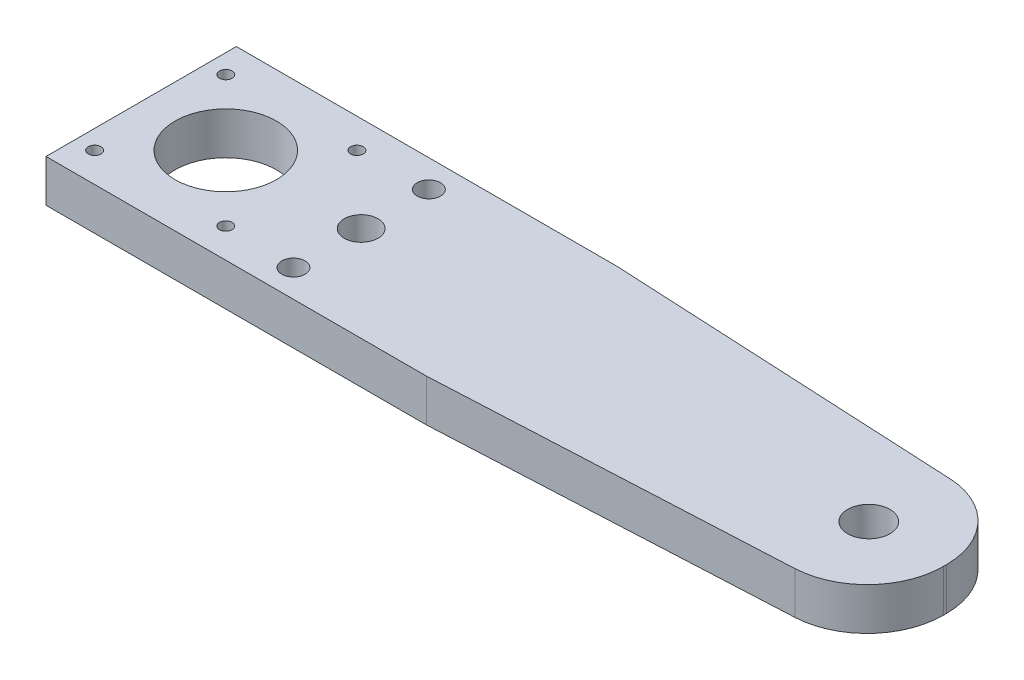
SolidWorks part; units mm, degrees
ref_plane "Front Plane" through (0, 0, 0) normal (0, 0, 1) x (1, 0, 0)
ref_plane "Top Plane" through (0, 0, 0) normal (0, 1, 0) x (1, 0, 0)
ref_plane "Right Plane" through (0, 0, 0) normal (1, 0, 0) x (0, 0, -1)
sketch "Sketch1" plane through (0, 0, 0) normal (0, 1, 0) x (1, 0, 0)
  line L1 (-95, 22.5) -> (95, 22.5)
  line L2 (-95, 22.5) -> (-95, -22.5)
  line L3 (-95, -22.5) -> (95, -22.5)
  line L4 (95, 22.5) -> (95, -22.5)
  line L5 (-95, 22.5) -> (95, -22.5) construction
  line L6 (-95, -22.5) -> (95, 22.5) construction
  point P0 (0, 0)
  dimension "D1" = 45
  dimension "D2" = 190
extrude "Boss-Extrude1" add sketch "Sketch1" along normal blind 10
sketch "Sketch2" plane through (0, 10, 0) normal (0, 1, 0) x (1, 0, 0)
  line L0 (-95, 0) -> (-75, 0) construction
  line L1 (-95, 22.5) -> (-95, -22.5) construction
  line L2 (-75, 0) -> (-43, 0) construction
  line L3 (-90.5, 15.5) -> (-59.5, 15.5) construction
  line L4 (-90.5, 15.5) -> (-90.5, -15.5) construction
  line L5 (-90.5, -15.5) -> (-59.5, -15.5) construction
  line L6 (-59.5, 15.5) -> (-59.5, -15.5) construction
  line L7 (-90.5, 15.5) -> (-59.5, -15.5) construction
  line L8 (-90.5, -15.5) -> (-59.5, 15.5) construction
  line L9 (-43, 0) -> (-43, 16) construction
  line L10 (-43, 0) -> (77, 0) construction
  circle A0 centre (-90.5, 15.5) radius 1.5
  circle A1 centre (-59.5, 15.5) radius 1.5
  circle A2 centre (-90.5, -15.5) radius 1.5
  circle A3 centre (-59.5, -15.5) radius 1.5
  circle A4 centre (-75, 0) radius 12
  circle A5 centre (-43, 0) radius 4
  circle A6 centre (-43, 16) radius 2.75
  circle A7 centre (-43, -16) radius 2.75
  circle A8 centre (77, 0) radius 5
  dimension "D3" = 3
  dimension "D4" = 3
  dimension "D5" = 3
  dimension "D6" = 3
  dimension "D7" = 24
  dimension "D9" = 8
  dimension "D11" = 5.5
  dimension "D13" = 10
  dimension "D1" = 20
  dimension "D2" = 31
  dimension "D8" = 32
  dimension "D10" = 16
  dimension "D12" = 120
extrude "Cut-Extrude1" cut sketch "Sketch2" against normal blind 10
sketch "Sketch3" plane through (0, 10, 0) normal (0, 1, 0) x (1, 0, 0)
  line L0 (95, -22.5) -> (-5, -22.5)
  line L1 (-95, -22.5) -> (95, -22.5) construction
  line L2 (95, -22.5) -> (95, -17.5)
  line L3 (95, -22.5) -> (95, 22.5) construction
  line L4 (-5, -22.5) -> (95, -17.5)
  line L5 (-5.5, 0) -> (5.5, 0) construction
  line L6 (-5, 22.5) -> (95, 17.5)
  line L7 (95, 22.5) -> (95, 17.5)
  line L8 (95, 22.5) -> (-5, 22.5)
  dimension "D1" = 100
  dimension "D2" = 5
extrude "Cut-Extrude2" cut sketch "Sketch3" against normal blind 10
fillet "Fillet1" radius 18 2 edges at (95, 5, -17.5) (95, 5, 17.5)
